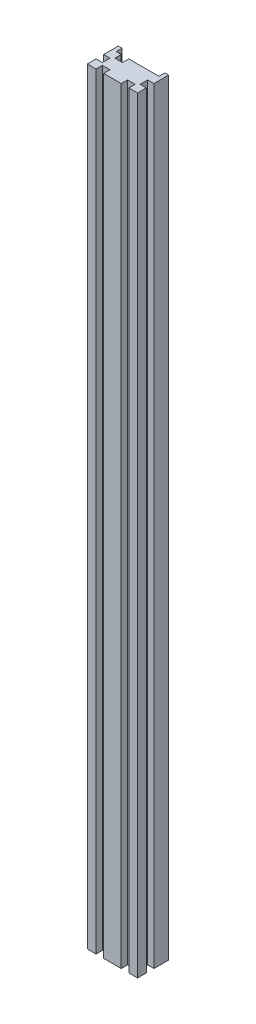
SolidWorks part; units mm, degrees
ref_plane "Front Plane" through (0, 0, 0) normal (0, 0, 1) x (1, 0, 0)
ref_plane "Top Plane" through (0, 0, 0) normal (0, 1, 0) x (1, 0, 0)
ref_plane "Right Plane" through (0, 0, 0) normal (1, 0, 0) x (0, 0, -1)
sketch "Sketch1" plane through (0, 0, 0) normal (0, 1, 0) x (1, 0, 0)
  line L1 (0, 0) -> (40, 0)
  line L2 (0, 0) -> (0, 20)
  line L3 (0, 20) -> (40, 20)
  line L4 (40, 0) -> (40, 20)
  dimension "D1" = 40
  dimension "D2" = 20
extrude "Boss-Extrude1" add sketch "Sketch1" along normal blind 609.6
sketch "Sketch2" plane through (0, 0, 0) normal (0, 0, 1) x (1, 0, 0)
  line L0 (0, 609.6) -> (40, 609.6) construction
  line L1 (7, 609.6) -> (13, 609.6)
  line L2 (7, 609.6) -> (7, 0)
  line L3 (7, 0) -> (13, 0)
  line L4 (13, 609.6) -> (13, 0)
  line L5 (0, 0) -> (40, 0) construction
  line L6 (0, 609.6) -> (0, 0) construction
  line L7 (27, 0) -> (33, 0)
  line L8 (27, 0) -> (27, 609.6)
  line L9 (27, 609.6) -> (33, 609.6)
  line L10 (33, 0) -> (33, 609.6)
  line L11 (40, 609.6) -> (40, 0) construction
  dimension "D1" = 7
  dimension "D2" = 7
  dimension "D3" = 14
extrude "Cut-Extrude1" cut sketch "Sketch2" against normal blind 5
sketch "Sketch3" plane through (0, 0, 0) normal (-1, 0, 0) x (0, 0, 1)
  line L0 (-20, 609.6) -> (0, 609.6) construction
  line L1 (-13, 609.6) -> (-7, 609.6)
  line L2 (-13, 609.6) -> (-13, 0)
  line L3 (-13, 0) -> (-7, 0)
  line L4 (-7, 609.6) -> (-7, 0)
  line L5 (-20, 0) -> (0, 0) construction
  line L6 (-20, 609.6) -> (-20, 0) construction
  dimension "D1" = 6
  dimension "D2" = 7
extrude "Cut-Extrude2" cut sketch "Sketch3" against normal blind 5
sketch "Sketch4" plane through (40, 0, 0) normal (1, 0, 0) x (0, 0, -1)
  line L0 (0, 609.6) -> (20, 609.6) construction
  line L1 (7, 609.6) -> (13, 609.6)
  line L2 (7, 609.6) -> (7, 0)
  line L3 (7, 0) -> (13, 0)
  line L4 (13, 609.6) -> (13, 0)
  line L5 (0, 0) -> (20, 0) construction
  line L6 (20, 609.6) -> (20, 0) construction
  dimension "D1" = 6
  dimension "D2" = 7
extrude "Cut-Extrude3" cut sketch "Sketch4" against normal blind 5
sketch "Sketch5" plane through (0, 0, -20) normal (0, 0, -1) x (-1, 0, 0)
  line L0 (-40, 609.6) -> (0, 609.6) construction
  line L1 (-7, 609.6) -> (-13, 609.6)
  line L2 (-7, 609.6) -> (-7, 0)
  line L3 (-7, 0) -> (-13, 0)
  line L4 (-13, 609.6) -> (-13, 0)
  line L5 (-40, 0) -> (0, 0) construction
  line L6 (0, 609.6) -> (0, 0) construction
  dimension "D1" = 6
  dimension "D2" = 7
extrude "Cut-Extrude4" cut sketch "Sketch5" against normal blind 5
sketch "Sketch6" plane through (0, 0, -20) normal (0, 0, -1) x (-1, 0, 0)
  line L0 (-40, 609.6) -> (-13, 609.6) construction
  line L1 (-40, 0) -> (-37, 0)
  line L2 (-40, 0) -> (-40, 609.6)
  line L3 (-40, 609.6) -> (-37, 609.6)
  line L4 (-37, 0) -> (-37, 609.6)
  line L5 (-7, 0) -> (0, 0) construction
  line L6 (0, 609.6) -> (-3, 609.6)
  line L7 (0, 609.6) -> (0, 0)
  line L8 (0, 0) -> (-3, 0)
  line L9 (-3, 609.6) -> (-3, 0)
  dimension "D1" = 3
  dimension "D2" = 3
extrude "Boss-Extrude2" add sketch "Sketch6" along normal blind 4.75
